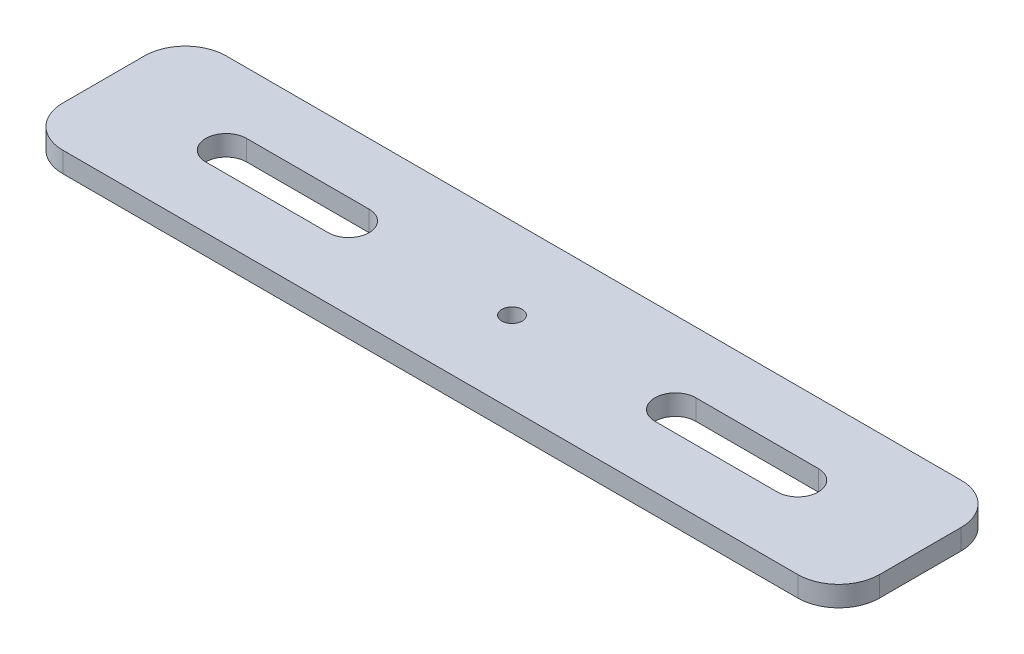
SolidWorks part; units mm, degrees
ref_plane "前视基准面" through (0, 0, 0) normal (0, 0, 1) x (1, 0, 0)
ref_plane "上视基准面" through (0, 0, 0) normal (0, 1, 0) x (1, 0, 0)
ref_plane "右视基准面" through (0, 0, 0) normal (1, 0, 0) x (0, 0, -1)
sketch "草图1" plane through (0, 0, 0) normal (0, 1, 0) x (1, 0, 0)
  line L0 (20, 20) -> (20, -20)
  line L1 (-20, -20) -> (20, -20)
  line L2 (-20, -20) -> (-20, 20)
  line L3 (-20, 20) -> (20, 20)
  line L4 (20, -20) -> (20, 20)
  line L5 (-20, -20) -> (20, 20) construction
  line L6 (-20, 20) -> (20, -20) construction
  line L7 (20, 20) -> (90, 20)
  line L8 (20, -20) -> (90, -20)
  line L9 (100, 10) -> (100, -10)
  line L10 (-20, 20) -> (-20, -20)
  line L11 (-20, 20) -> (-90, 20)
  line L12 (-20, -20) -> (-90, -20)
  line L13 (-100, 10) -> (-100, -10)
  line L14 (-40, 0) -> (-70, 0) construction
  line L15 (-40, -5) -> (-70, -5)
  line L16 (-40, 5) -> (-70, 5)
  line L17 (40, 0) -> (70, 0) construction
  line L18 (40, 5) -> (70, 5)
  line L19 (40, -5) -> (70, -5)
  arc A0 (90, -20) -> (100, -10) centre (90, -10) ccw
  arc A1 (90, 20) -> (100, 10) centre (90, 10) cw
  arc A2 (-90, 20) -> (-100, 10) centre (-90, 10) ccw
  arc A3 (-100, -10) -> (-90, -20) centre (-90, -10) ccw
  circle A4 centre (0, 0) radius 2.5
  arc A7 (-40, -5) -> (-40, 5) centre (-40, 0) ccw
  arc A8 (-70, 5) -> (-70, -5) centre (-70, 0) ccw
  arc A9 (40, 5) -> (40, -5) centre (40, 0) ccw
  arc A10 (70, -5) -> (70, 5) centre (70, 0) ccw
  point P0 (0, 0)
  point P5 (-55, 0)
  point P30 (55, 0)
extrude "凸台-拉伸3" add sketch "草图1" along normal blind 5 contours L13 A3 L12 L2 L11 A2 A8 L16 A7 L15 | L3 L2 L1 L0 A4 | A1 L7 L0 L8 A0 L9 A10 L19 A9 L18
